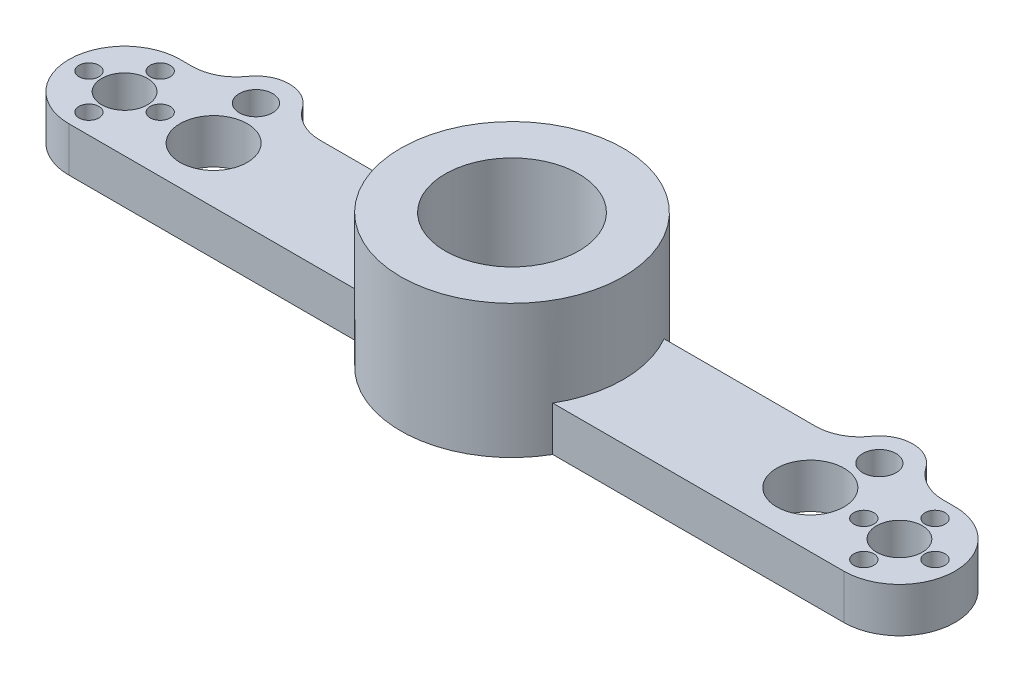
SolidWorks part; units mm, degrees
ref_plane "Plan de face" through (0, 0, 0) normal (0, 0, 1) x (1, 0, 0)
ref_plane "Plan de dessus" through (0, 0, 0) normal (0, 1, 0) x (1, 0, 0)
ref_plane "Plan de droite" through (0, 0, 0) normal (1, 0, 0) x (0, 0, -1)
sketch "Esquisse1" plane through (0, 0, 0) normal (0, 1, 0) x (1, 0, 0)
  line L0 (-87, 0) -> (87, 0) construction
  line L1 (87, -12.5) -> (21.6506, -12.5)
  line L2 (-87, 12.5) -> (-21.6506, 12.5)
  line L3 (-21.6506, -12.5) -> (-87, -12.5)
  line L4 (21.6506, 12.5) -> (87, 12.5)
  circle A0 centre (-87, 0) radius 5.15
  circle A1 centre (87, 0) radius 5.15
  arc A2 (-87, 12.5) -> (-87, -12.5) centre (-87, 0) ccw
  arc A3 (87, -12.5) -> (87, 12.5) centre (87, 0) ccw
  arc A4 (-21.6506, -12.5) -> (21.6506, -12.5) centre (0, 0) ccw
  arc A6 (21.6506, 12.5) -> (-21.6506, 12.5) centre (0, 0) ccw
  circle A7 centre (0, 0) radius 15
  dimension "D2" = 10.3
  dimension "D3" = 25
  dimension "D4" = 10
  dimension "D5" = 50
  dimension "D1" = 174
extrude "Boss.-Extru.1" add sketch "Esquisse1" along normal blind 10
hole_wizard "Diamètre du perçage Ø4.5 (4.5)1" positions "Esquisse2" profile "Esquisse3" hole size "Ø4.5" standard "Ansi Metric" end condition through all
sketch "Esquisse2" plane through (0, 10, 0) normal (0, 1, 0) x (1, 0, 0)
  line L0 (-87, 0) -> (-87, 8) construction
  point P2 (-87, 8)
  dimension "D1" = 8
sketch "Esquisse3" plane through (-87, 10, -8) normal (1, 0, 0) x (0, 0, 1)
  line L0 (0, 0) -> (0, 10)
  line L1 (0, 10) -> (2.25, 10)
  line L2 (2.25, 10) -> (2.25, 0)
  line L5 (2.25, 0) -> (0, 0)
  line L11 (0, -6.35) -> (0, 107.95) construction
  dimension "Diamètre du perçage jusqu'au prochain" = 4.5
  dimension "Profondeur du perçage jusqu'au prochain" = 10
pattern_circular "Répétition circulaire1" count 4 over 360 about axis through (-87, 0, 0) along (0, 1, 0) of "Diamètre du perçage Ø4.5 (4.5)1"
sketch "Esquisse4" plane through (0, 10, 0) normal (0, 1, 0) x (1, 0, 0)
  line L0 (-87, 0) -> (-67, 0) construction
  circle A0 centre (-67, 0) radius 7.55
  circle A2 centre (-87, 0) radius 11 construction
  dimension "D1" = 15.1
  dimension "D2" = 22
  dimension "D3" = 20
extrude "Enlèv. mat.-Extru.1" cut sketch "Esquisse4" against normal through all
mirror "Symétrie1" about plane through (0, 0, 0) normal (1, 0, 0) of "Répétition circulaire1", "Diamètre du perçage Ø4.5 (4.5)1", "Enlèv. mat.-Extru.1"
sketch "Esquisse7" plane through (0, 10, 0) normal (0, 1, 0) x (1, 0, 0)
  circle A0 centre (0, 0) radius 25
  circle A1 centre (0, 0) radius 15
  circle A2 centre (0, 0) radius 15 construction
extrude "Boss.-Extru.3" add sketch "Esquisse7" along normal blind 20
sketch "Esquisse8" plane through (0, 10, 0) normal (0, 1, 0) x (1, 0, 0)
  line L0 (87, 12.5) -> (21.6506, 12.5) construction
  line L1 (62.5, 12.5) -> (77.5, 12.5)
  line L3 (0, 0) -> (0, 15) construction
  line L4 (-62.5, 12.5) -> (-77.5, 12.5)
  arc A0 (77.5, 12.5) -> (62.5, 12.5) centre (70, 12.5) ccw
  circle A2 centre (87, 8) radius 2.25 construction
  circle A3 centre (0, 0) radius 15 construction
  arc A4 (-77.5, 12.5) -> (-62.5, 12.5) centre (-70, 12.5) cw
  dimension "D1" = 17
  dimension "D2" = 15
extrude "Boss.-Extru.4" add sketch "Esquisse8" against normal through all
hole_wizard "Chambrage pour vis à tête ronde bombée M31" positions "Esquisse9" profile "Esquisse10" counterbore size "M3" standard "Ansi Metric" end condition through all
sketch "Esquisse9" plane through (0, 10, 0) normal (0, 1, 0) x (1, 0, 0)
  point P0 (70, 12.5)
  point P3 (-70, 12.5)
sketch "Esquisse10" plane through (70, 10, -12.5) normal (1, 0, 0) x (0, 0, 1)
  line L0 (0, 0) -> (0, 10)
  line L1 (0, 10) -> (1.7, 10)
  line L3 (1.7, 10) -> (1.7, 6.4)
  line L4 (1.7, 6.4) -> (3.75, 6.4)
  line L5 (3.75, 6.4) -> (3.75, 0)
  line L7 (3.75, 0) -> (0, 0)
  line L11 (0, -6.35) -> (0, 107.95) construction
  dimension "Diamètre du perçage jusqu'au prochain" = 3.4
  dimension "Profondeur du perçage jusqu'au prochain" = 10
  dimension "Diamètre du chambrage" = 7.5
  dimension "Profondeur du chambrage" = 6.4
fillet "Congé1" radius 10 4 edges at (77.5, 5, -12.5) (62.5, 5, -12.5) (-62.5, 5, -12.5) (-77.5, 5, -12.5)
